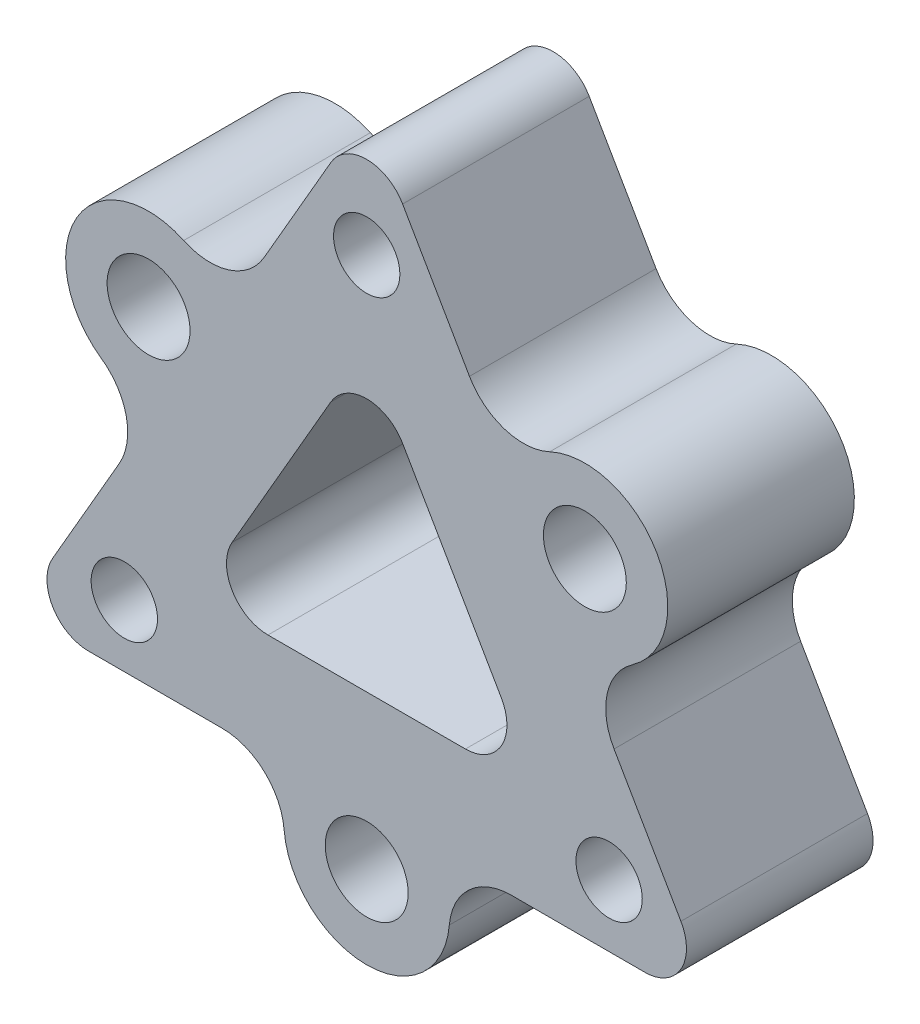
SolidWorks part; units mm, degrees
material "Thornel Mat VMA"
ref_plane "前视基准面" through (0, 0, 0) normal (0, 0, 1) x (1, 0, 0)
ref_plane "上视基准面" through (0, 0, 0) normal (0, 1, 0) x (1, 0, 0)
ref_plane "右视基准面" through (0, 0, 0) normal (1, 0, 0) x (0, 0, -1)
sketch "草图1" plane through (0, 0, 0) normal (0, 0, 1) x (1, 0, 0)
  line L0 (0, 19.5) -> (-16.8875, -9.75)
  line L1 (0, 13.5) -> (-11.6913, -6.75) construction
  line L2 (-11.6913, -6.75) -> (11.6913, -6.75) construction
  line L3 (11.6913, -6.75) -> (0, 13.5) construction
  line L4 (-16.8875, -9.75) -> (16.8875, -9.75)
  line L5 (16.8875, -9.75) -> (0, 19.5)
  line L6 (8.2272, -4.75) -> (0, 9.5)
  line L7 (0, 9.5) -> (-8.2272, -4.75)
  line L8 (-8.2272, -4.75) -> (8.2272, -4.75)
  circle A0 centre (0, 0) radius 13.5 construction
  circle A1 centre (0, 13.5) radius 1.6
  circle A2 centre (11.6913, -6.75) radius 1.6
  circle A3 centre (-11.6913, -6.75) radius 1.6
  dimension "D2" = 27
  dimension "D3" = 3.2
  dimension "D1" = 3
  dimension "D4" = 2
extrude "凸台-拉伸1" add sketch "草图1" along normal blind 9
fillet "圆角1" radius 2 6 edges at (0, 9.5, 4.5) (-8.2272, -4.75, 4.5) (8.2272, -4.75, 4.5) (16.8875, -9.75, 4.5) (-16.8875, -9.75, 4.5) (0, 19.5, 4.5)
sketch "草图2" plane through (0, 0, 9) normal (0, 0, 1) x (1, 0, 0)
  circle A0 centre (0, 0) radius 12.15 construction
  circle A1 centre (0, -12.15) radius 2
  circle A2 centre (-10.5222, 6.075) radius 2
  circle A3 centre (10.5222, 6.075) radius 2
  circle A4 centre (10.5222, 6.075) radius 4
  circle A5 centre (-10.5222, 6.075) radius 4
  circle A6 centre (0, -12.15) radius 4
  point P5 (16.7887, 9.8074)
  point P6 (0, 0)
  point P12 (0, 0)
  dimension "D1" = 24.3
  dimension "D2" = 4
  dimension "D4" = 2
  dimension "D3" = 3
extrude "凸台-拉伸2" add sketch "草图2" against normal up to surface (9 mm away) up to face at (1.6, 13.5, 0)
fillet "圆角2" radius 3 6 edges at (10.0437, 2.1037, 4.5) (6.8437, 7.6463, 4.5) (-6.8437, 7.6463, 4.5) (-10.0437, 2.1037, 4.5) (-3.2, -9.75, 4.5) (3.2, -9.75, 4.5)
